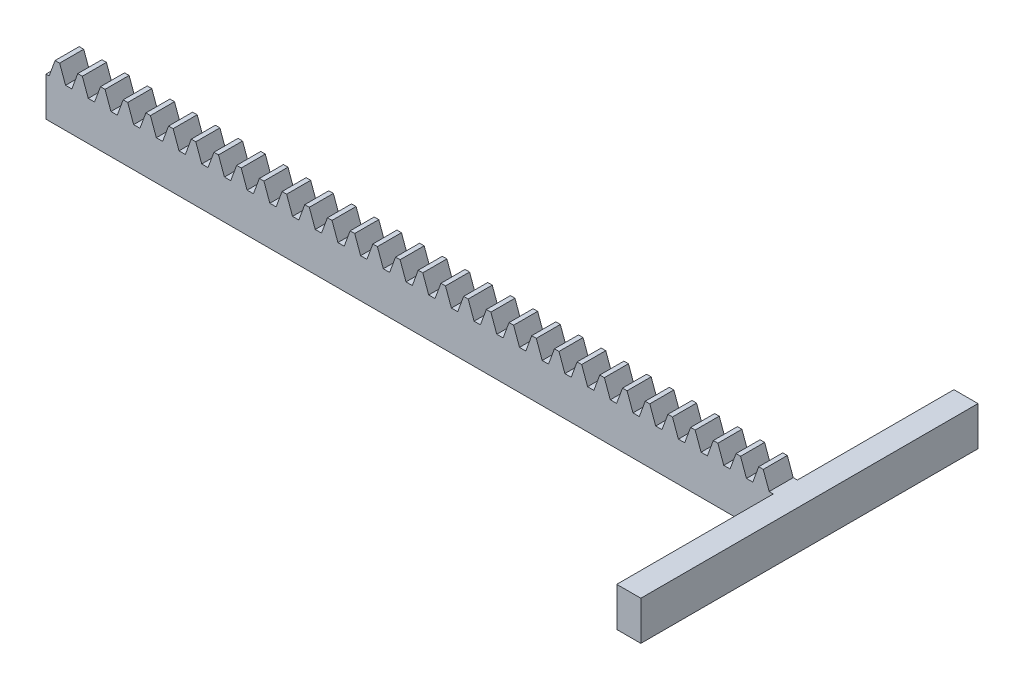
SolidWorks part; units mm, degrees
extrude "Blank" add sketch "BlankSke" against normal blind 5
sketch "BlankSke" plane through (0, 0, 0) normal (0, 0, 1) x (1, 0, 0)
  line L1 (0, 0) -> (151, 0)
  line L2 (0, 0) -> (0, 11.5)
  line L3 (0, 11.5) -> (151, 11.5)
  line L4 (151, 0) -> (151, 11.5)
  dimension "Length" = 151
  dimension "Blank_height" = 11.5
ref_plane "Plane1" through (0, 0, 0) normal (0, 0, 1) x (1, 0, 0)
ref_plane "Plane2" through (0, 0, 0) normal (0, 1, 0) x (1, 0, 0)
ref_plane "Plane3" through (0, 0, 0) normal (1, 0, 0) x (0, 0, -1)
sketch "HoldingSke" plane through (0, 0, 0) normal (0, 1, 0) x (1, 0, 0)
  line L0 (0, 0) -> (0.0928, 0.6602)
  line L1 (-15, 0) -> (100, 0) construction
  line L2 (0, 0) -> (-2.1039, 2.3779)
  line L3 (0, 0) -> (-11.863, 4.5341)
  line L4 (0, 0) -> (7.1596, 4.8292)
  line L5 (0, 0) -> (-23.7986, -8.8762)
  line L6 (0, 0) -> (-10.5278, -7.1032)
  line L9 (-71.009, 38.7566) -> (70.8846, 90.4017)
  line L10 (-76.2, 3.8779) -> (-66.2, 3.8779)
  line L11 (0, 0) -> (-5, 0)
  line L12 (-76.2, 101.6) -> (-76.147, 101.6)
  line L13 (24.9733, 27.94) -> (52.9518, 28.4284)
  line L14 (24.9733, 27.94) -> (24.9743, 27.94)
  line L15 (24.9733, 27.94) -> (100.4006, 29.5858)
  circle A0 centre (0, 0) radius 19.05
  circle A1 centre (0, 0) radius 5
  circle A2 centre (0, 0) radius 12.7
  dimension "MPH" = 10
  dimension "Diameter" = 38.1
  dimension "Num_teeth" = 34
  dimension "Pitch" = 0.6667
  dimension "Show_teeth" = 998
  dimension "Thickness" = 12.7
  dimension "Ap" = 20
  dimension "Pitch_height" = 10
  dimension "Width" = 5
  dimension "Backlash" = 0.053
  dimension "Addendum_fac" = 1
  dimension "Dedendum_fac" = 1.25
  dimension "Clearance_fac" = 0.25
  dimension "Dedendum_add" = 0.001
  dimension "Length" = 151
  dimension "Module" = 1.5
sketch "TooCutSkeIll" plane through (0, 0, 0) normal (0, 0, 1) x (1, 0, 0)
  line L0 (-1.8687, 11.4605) -> (-0.7447, 8.3724)
  line L1 (-0.3914, 8.125) -> (0.3914, 8.125)
  line L2 (0.7447, 8.3724) -> (1.8687, 11.4605)
  line L3 (151, 11.5) -> (0, 11.5) construction
  line L4 (0, 0) -> (0, 64.897) construction
  line L5 (-13.208, 10) -> (12.954, 10) construction
  line L6 (0, 0) -> (151, 0) construction
  line L7 (1.3371, 10) -> (1.3371, 48.7463) construction
  line L8 (-1.3371, 10) -> (-1.3371, 48.7463) construction
  line L9 (1.9251, 11.5) -> (1.9251, 11.5254)
  line L10 (-1.9251, 11.5) -> (-1.9251, 11.5254)
  line L11 (-1.9251, 11.5254) -> (1.9251, 11.5254)
  arc A0 (0.3914, 8.125) -> (0.7447, 8.3724) centre (0.3914, 8.501) ccw
  arc A1 (-0.7447, 8.3724) -> (-0.3914, 8.125) centre (-0.3914, 8.501) ccw
  arc A2 (1.9251, 11.5) -> (1.8687, 11.4605) centre (1.9251, 11.44) ccw
  arc A3 (-1.8687, 11.4605) -> (-1.9251, 11.5) centre (-1.9251, 11.44) ccw
  dimension "Pitch_height" = 10
  dimension "Addendum_plus" = 1.5254
  dimension "Pressure_angle" = 20
  dimension "Gap_width" = 2.6742
  dimension "Dedendum" = 1.875
extrude "ToothCutIll" [suppressed] cut sketch "TooCutSkeIll" against normal through all
sketch "TooCutSkeSim" plane through (0, 0, 0) normal (0, 0, 1) x (1, 0, 0)
  line L0 (0.6547, 8.125) -> (-0.6547, 8.125)
  line L1 (1.8923, 11.5254) -> (0.6547, 8.125)
  line L2 (0, 17.4625) -> (0, 53.467) construction
  line L3 (1.8923, 11.5254) -> (-1.8923, 11.5254)
  line L6 (-1.8923, 11.5254) -> (-0.6547, 8.125)
  line L9 (-1.3371, 10) -> (1.3371, 10) construction
  line L10 (0, 0) -> (151, 0) construction
  line L11 (1.3371, 10) -> (1.3371, 53.467) construction
  line L12 (-1.3371, 10) -> (-1.3371, 53.467) construction
  dimension "Pitch_height" = 10
  dimension "Addendum_plus" = 1.5254
  dimension "Pressure_angle" = 20
  dimension "Gap_width" = 2.6742
  dimension "Dedendum" = 1.875
extrude "ToothCutSim" cut sketch "TooCutSkeSim" against normal through all
pattern_linear "TeethCuts" count 33 spacing 4.7124 along (1, 0, 0) of "ToothCutIll", "ToothCutSim"
sketch "Croquis1" plane through (151, 0, 0) normal (1, 0, 0) x (0, 0, -1)
  line L0 (2.5, 8.125) -> (2.5, 0) construction
  line L3 (0, 8.125) -> (5, 8.125) construction
  line L4 (5, 0) -> (0, 0) construction
  line L6 (-32.5, 0) -> (37.5, 0)
  line L7 (-32.5, 0) -> (-32.5, 8.125)
  line L8 (-32.5, 8.125) -> (37.5, 8.125)
  line L9 (37.5, 0) -> (37.5, 8.125)
  line L10 (-32.5, 0) -> (37.5, 8.125) construction
  line L11 (-32.5, 8.125) -> (37.5, 0) construction
  point P6 (2.5, 4.0625)
  dimension "D1" = 70
extrude "Saliente-Extruir1" add sketch "Croquis1" along normal blind 5
sketch "Croquis3" plane through (0, 0, 0) normal (0, 0, 1) x (1, 0, 0)
  line L0 (45.855, 9.8125) -> (90.8042, 9.8125) construction
  line L1 (46.4692, 8.125) -> (45.2408, 11.5) construction
  line L2 (90.19, 8.125) -> (91.4184, 11.5) construction
equation "' \"Module@HoldingSke\" = 6.35"
equation "' \"Num_teeth@HoldingSke\" = 12"
equation "' \"Ap@HoldingSke\" =  20"
equation "' \"Ap@HoldingSke\" = 20"
equation "' \"Width@HoldingSke\" = 0.25 * 25.4"
equation "' \"Show_teeth@HoldingSke\" = 500"
equation "' \"Backlash@HoldingSke\" = 0.009 * 25.4"
equation "' \"Addendum_fac@HoldingSke\" = 1.0"
equation "' \"Dedendum_fac@HoldingSke\" = 1.25"
equation "' \"Dedendum_add@HoldingSke\" = 0.00005 * 25.4"
equation "' \"Clearance_fac@HoldingSke\" = 0.25"
equation "' \"Pitch_height@HoldingSke\" = 1 * 25.4"
equation "' \"Length@HoldingSke\" = 4.71 * 25.4"
equation "\"Pitch@HoldingSke\" = 1 / \"Module@HoldingSke\""
equation "\"MPH@HoldingSke\" = \"Dedendum_fac@HoldingSke\" / \"Pitch@HoldingSke\" + 2 * \"Dedendum_add@HoldingSke\" + 0.002 * 25.4"
equation "\"MPH@HoldingSke\" = ((sgn( \"MPH@HoldingSke\" - \"Pitch_height@HoldingSke\")+1)*( \"MPH@HoldingSke\" - \"Pitch_height@HoldingSke\"))/2 + \"Pitch_height@HoldingSke\""
equation "\"Blank_height@BlankSke\" = \"Pitch_height@HoldingSke\" + \"Addendum_fac@HoldingSke\"  / \"Pitch@HoldingSke\" "
equation "\"Length@BlankSke\" =  \"Length@HoldingSke\""
equation "\"Face_width@Blank\" = \"Width@HoldingSke\""
equation "\"Pressure_angle@TooCutSkeIll\" = \"Ap@HoldingSke\""
equation "\"Addendum_plus@TooCutSkeIll\" =  \"Addendum_fac@HoldingSke\"  / \"Pitch@HoldingSke\" + 0.001 *25.4"
equation "\"Dedendum@TooCutSkeIll\" = \"Dedendum_fac@HoldingSke\"  / \"Pitch@HoldingSke\""
equation "\"Pitch_height@TooCutSkeIll\" =  \"MPH@HoldingSke\""
equation "\"Gap_width@TooCutSkeIll\" = 3.14159265 / 2 / \"Pitch@HoldingSke\" + 6 * \"Backlash@HoldingSke\""
equation "\"Pressure_angle@TooCutSkeSim\" = \"Ap@HoldingSke\""
equation "\"Addendum_plus@TooCutSkeSim\" =  \"Addendum_fac@HoldingSke\"  / \"Pitch@HoldingSke\" + 0.001 * 25.4"
equation "\"Dedendum@TooCutSkeSim\" = \"Dedendum_fac@HoldingSke\"  / \"Pitch@HoldingSke\""
equation "\"Pitch_height@TooCutSkeSim\" =  \"MPH@HoldingSke\""
equation "\"Gap_width@TooCutSkeSim\" = 3.14159265 / 2 / \"Pitch@HoldingSke\" + 6 * \"Backlash@HoldingSke\""
equation "\"Root_fillet@TooCutSkeIll\" = \"Clearance_fac@HoldingSke\" / \"Pitch@HoldingSke\" + \"Dedendum_add@HoldingSke\""
equation "\"Break_rad@TooCutSkeIll\" = 0.02 / \"Pitch@HoldingSke\" * 2"
equation "\"Linear_pitch@TeethCuts\" = 3.14159265 / \"Pitch@HoldingSke\""
equation "\"Num_teeth@HoldingSke\" = int( ( \"Length@HoldingSke\" + 0 ) / (3.14159265 / \"Pitch@HoldingSke\")) + 0.9999  + 1"
equation " \"Num_teeth@TeethCuts\" = int( \"Show_teeth@HoldingSke\" ) + 1"
equation " \"Num_teeth@TeethCuts\" = ((sgn( \"Num_teeth@TeethCuts\" - \"Num_teeth@HoldingSke\" )-1)*( \"Num_teeth@TeethCuts\" - \"Num_teeth@HoldingSke\" ))/-2+ \"Num_teeth@HoldingSke\""
equation " \"Num_teeth@TeethCuts\" = ((sgn( \"Num_teeth@TeethCuts\" - 2.0)+1)*( \"Num_teeth@TeethCuts\" - 2.0))/2 +2.0"
